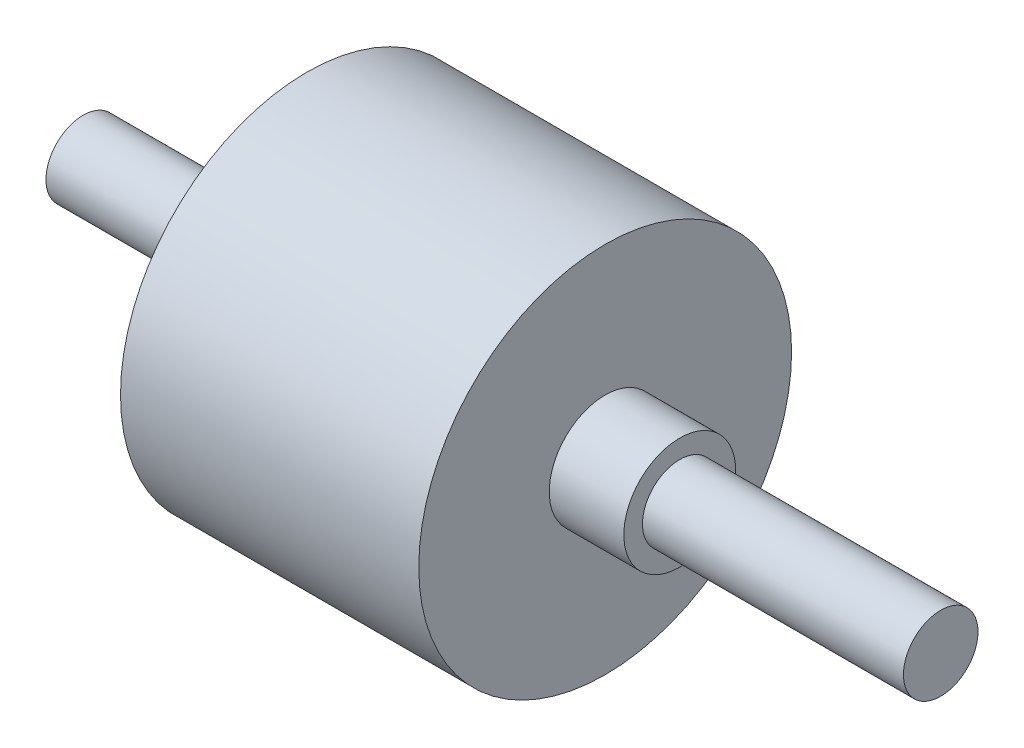
SolidWorks part; units mm, degrees
ref_plane "Front Plane" through (0, 0, 0) normal (1, 0, 0) x (0, 1, 0)
ref_plane "Top Plane" through (0, 0, 0) normal (0, 0, 1) x (0, 1, 0)
ref_plane "Right Plane" through (0, 0, 0) normal (0, 1, 0) x (-1, 0, 0)
sketch "Sketch1" plane through (0, 0, 0) normal (1, 0, 0) x (0, 1, 0)
  circle A0 centre (0, 0) radius 25
  dimension "D1" = 50
extrude "Boss-Extrude1" add sketch "Sketch1" along normal blind 40
sketch "Sketch2" plane through (40, 0, 0) normal (1, 0, 0) x (0, 1, 0)
  circle A0 centre (0, 0) radius 7.5
  dimension "D1" = 15
extrude "Boss-Extrude2" add sketch "Sketch2" along normal blind 10
sketch "Sketch3" plane through (50, 0, 0) normal (1, 0, 0) x (0, 1, 0)
  circle A0 centre (0, 0) radius 5
  dimension "D1" = 10
extrude "Boss-Extrude3" add sketch "Sketch3" along normal blind 35 and the other way blind 80
